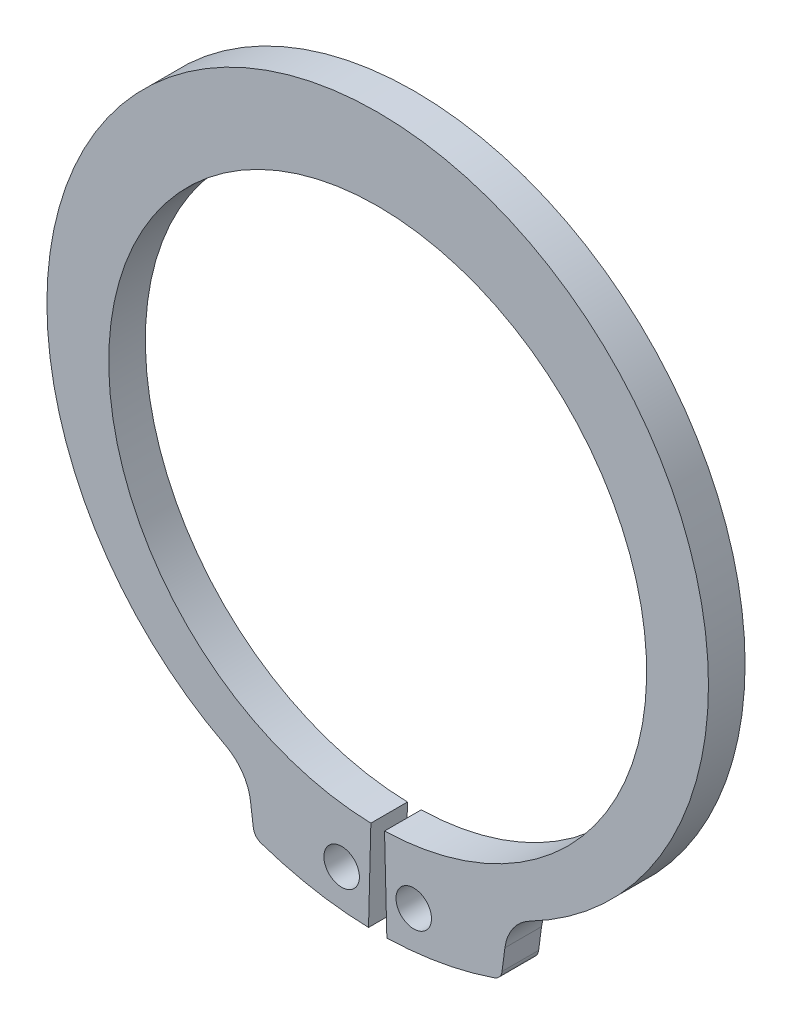
SolidWorks part; units mm, degrees
ref_plane "Plane1" through (0, 0, 0) normal (0, 0, 1) x (1, 0, 0)
ref_plane "Plane2" through (0, 0, 0) normal (0, 1, 0) x (1, 0, 0)
ref_plane "Plane3" through (0, 0, 0) normal (1, 0, 0) x (0, 0, -1)
sketch "Clipboard" plane through (0, 0, 0) normal (0, 0, 1) x (1, 0, 0)
  line L0 (0, 0) -> (7.1, 0)
  line L1 (0, 0) -> (0, 3.9)
  line L2 (0, 0) -> (0, -8)
  circle A0 centre (0, 0) radius 1.55
  circle A1 centre (0, 0) radius 25
  dimension "HoleDia" = 3.1
  dimension "ShaftDia" = 50
  dimension "LargeSection" = 7.1
  dimension "SmallSection" = 3.9
  dimension "LugSection" = 8
sketch "BodySke" plane through (0, 0, 0) normal (0, 0, 1) x (1, 0, 0)
  line L0 (-1.5431, 0) -> (1.5431, 0) construction
  line L1 (0, 0) -> (0, 30.6) construction
  line L2 (0.5968, -23.4924) -> (0.8, -31.4898)
  line L3 (-0.5968, -23.4924) -> (-0.8, -31.4898)
  line L4 (0, 0) -> (15.1797, -27.6012) construction
  line L5 (0, 0) -> (-15.1797, -27.6012) construction
  line L7 (11.1162, -27.0663) -> (10.8631, -28.9888)
  line L8 (-11.1162, -27.0663) -> (-10.8631, -28.9888)
  circle A0 centre (0, 0) radius 23.5 construction
  arc A1 (0.5968, -23.4924) -> (-0.5968, -23.4924) centre (0, 0) ccw
  arc A2 (13.2039, -24.0087) -> (-13.2039, -24.0087) centre (0, 1.6994) ccw construction
  arc A3 (0.8, -31.4898) -> (10.1953, -29.8045) centre (0, 0) ccw
  arc A4 (13.2943, -23.962) -> (11.1162, -27.0663) centre (15.1797, -27.6012) ccw
  arc A5 (-11.1162, -27.0663) -> (-13.2943, -23.962) centre (-15.1797, -27.6012) ccw
  arc A6 (-10.1953, -29.8045) -> (-0.8, -31.4898) centre (0, 0) ccw
  arc A7 (13.2943, -23.962) -> (-13.2943, -23.962) centre (0, 1.6994) ccw
  arc A8 (-11.2691, -25.905) -> (11.2691, -25.905) centre (0, 0) ccw construction
  circle A9 centre (3.15, -28.0738) radius 1.55
  circle A10 centre (-3.15, -28.0738) radius 1.55
  arc A11 (10.8631, -28.9888) -> (10.1953, -29.8045) centre (9.8716, -28.8583) cw
  arc A12 (-10.8631, -28.9888) -> (-10.1953, -29.8045) centre (-9.8716, -28.8583) ccw
  point P28 (10.783, -29.5969)
  point P31 (-10.783, -29.5969)
  dimension "GrooveDia" = 47
  dimension "LugRad" = 31.5
  dimension "HoleOffsetRad" = 28.25
  dimension "HoleDia" = 3.1
  dimension "D3" = 1
  dimension "LargeRad" = 30.6
  dimension "SmallRad" = 27.4
  dimension "SmallAngle" = 57.618
  dimension "D2" = 15
  dimension "HoleSpacing" = 6.3
  dimension "Gap" = 1.6
extrude "Body" add sketch "BodySke" against normal blind 3.2
sketch "NotSke" plane through (0, 0, 0) normal (0, 0, 1) x (1, 0, 0)
  line L0 (3.15, -26.5238) -> (3.15, -29.6238)
  line L1 (3.15, -29.6238) -> (-3.15, -29.6238)
  line L2 (-3.15, -29.6238) -> (-3.15, -26.5238)
  line L3 (-3.15, -26.5238) -> (3.15, -26.5238)
  circle A0 centre (3.15, -28.0738) radius 1.55 construction
  circle A1 centre (-3.15, -28.0738) radius 1.55 construction
extrude "Notch" [suppressed] cut sketch "NotSke" against normal through all
equation "' \"ShaftDia@Clipboard\" = 10"
equation "' \"Thickness@Body\" = 0.9"
equation "' \"GrooveDia@BodySke\" = 9.4"
equation "' \"LugSection@Clipboard\" = 2.6"
equation "' \"LargeSection@Clipboard\" = 1.7"
equation "' \"SmallSection@Clipboard\" = 1.0"
equation "' \"HoleDia@Clipboard\" = 1.0"
equation "' \"ShaftDia@Clipboard\" = 30"
equation "' \"Thickness@Body\" = 2.4"
equation "' \"GrooveDia@BodySke\" = 28.2"
equation "' \"LugSection@Clipboard\" = 5.6"
equation "' \"LargeSection@Clipboard\" = 4.5"
equation "' \"SmallSection@Clipboard\" = 2.5"
equation "' \"HoleDia@Clipboard\" = 2.3"
equation "\"Gap@BodySke\" =  \"Thickness@Body\" / 2"
equation "\"LargeRad@BodySke\" =  \"GrooveDia@BodySke\" / 2 +  \"LargeSection@Clipboard\""
equation "\"SmallRad@BodySke\" =  \"GrooveDia@BodySke\" / 2 +  \"SmallSection@Clipboard\""
equation "\"LugRad@BodySke\" = \"GrooveDia@BodySke\" / 2 + \"LugSection@Clipboard\""
equation "\"HoleOffsetRad@BodySke\" = (  \"ShaftDia@Clipboard\" / 2 + \"LugRad@BodySke\" ) / 2"
equation "\"HoleSpacing@BodySke\" = \"Gap@BodySke\"  * 2 +  \"HoleDia@Clipboard\""
equation "\"HoleDia@BodySke\" =  \"HoleDia@Clipboard\""
equation "\"SmallAngle@BodySke\" = atn(\"HoleSpacing@BodySke\" / 2 / sqr(\"HoleOffsetRad@BodySke\"  * \"HoleOffsetRad@BodySke\" - (\"HoleSpacing@BodySke\" / 2) * (\"HoleSpacing@BodySke\" / 2) ))  * 9 * ( 180 / 3.141593)"
